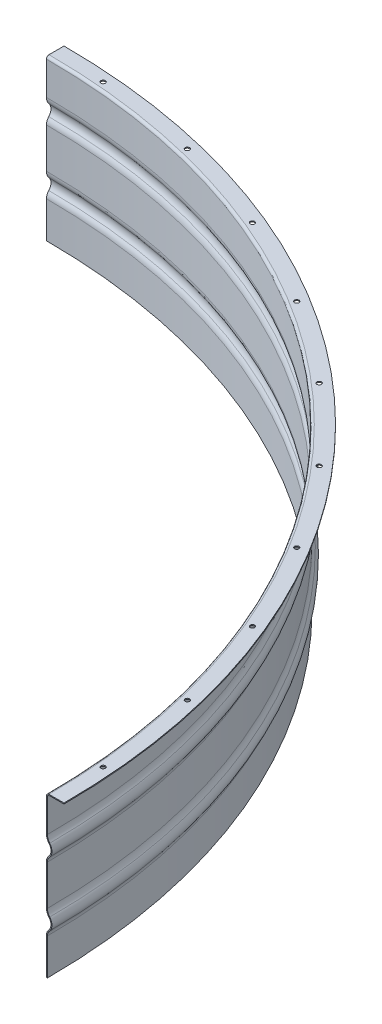
SolidWorks part; units mm, degrees
ref_plane "Front Plane" through (0, 0, 0) normal (0, 0, 1) x (1, 0, 0)
ref_plane "Top Plane" through (0, 0, 0) normal (0, 1, 0) x (1, 0, 0)
ref_plane "Right Plane" through (0, 0, 0) normal (1, 0, 0) x (0, 0, -1)
sketch "Sketch1" plane through (0, 0, 0) normal (1, 0, 0) x (0, 0, -1)
  line L0 (1713.6591, 1048.0054) -> (1666.6591, 1048.0054)
  line L1 (1658.6591, 1040.0054) -> (1658.6591, 936.4391)
  line L2 (1658.6591, 861.8519) -> (1658.6591, 736.4391)
  line L3 (1658.6591, 661.8519) -> (1658.6591, 548.0054)
  line L4 (1713.6591, 1045.0054) -> (1666.6591, 1045.0054)
  line L5 (1661.6591, 1040.0054) -> (1661.6591, 936.4391)
  line L6 (1661.6591, 861.8519) -> (1661.6591, 736.4391)
  line L7 (1661.6591, 661.8519) -> (1661.6591, 548.0054)
  line L8 (1661.6591, 548.0054) -> (1658.6591, 548.0054)
  line L9 (1713.6591, 1048.0054) -> (1713.6591, 1045.0054)
  line L10 (-336.3409, 1001.4955) -> (-336.3409, 321.842)
  arc A0 (1666.6591, 1048.0054) -> (1658.6591, 1040.0054) centre (1666.6591, 1040.0054) ccw
  arc A1 (1658.6591, 936.4391) -> (1666.68, 914.6889) centre (1692.1591, 936.4391) ccw
  arc A2 (1665.9861, 880.5416) -> (1666.68, 914.6889) centre (1647.1363, 898.0054) ccw
  arc A3 (1665.9861, 880.5416) -> (1658.6591, 861.8519) centre (1686.1591, 861.8519) ccw
  arc A4 (1658.6591, 736.4391) -> (1666.68, 714.6889) centre (1692.1591, 736.4391) ccw
  arc A5 (1665.9861, 680.5416) -> (1666.68, 714.6889) centre (1647.1363, 698.0054) ccw
  arc A6 (1665.9861, 680.5416) -> (1658.6591, 661.8519) centre (1686.1591, 661.8519) ccw
  arc A7 (1666.6591, 1045.0054) -> (1661.6591, 1040.0054) centre (1666.6591, 1040.0054) ccw
  arc A8 (1661.6591, 936.4391) -> (1668.9617, 916.6367) centre (1692.1591, 936.4391) ccw
  arc A9 (1668.1868, 878.5027) -> (1668.9617, 916.6367) centre (1647.1363, 898.0054) ccw
  arc A10 (1668.1868, 878.5027) -> (1661.6591, 861.8519) centre (1686.1591, 861.8519) ccw
  arc A11 (1661.6591, 736.4391) -> (1668.9617, 716.6367) centre (1692.1591, 736.4391) ccw
  arc A12 (1668.1868, 678.5027) -> (1668.9617, 716.6367) centre (1647.1363, 698.0054) ccw
  arc A13 (1668.1868, 678.5027) -> (1661.6591, 661.8519) centre (1686.1591, 661.8519) ccw
revolve "Revolve1" add sketch "Sketch1" angle 90 about L10
sketch "Sketch2" plane through (0, 1048.0054, 0) normal (0, 1, 0) x (1, 0, 0)
  circle A1 centre (158.4874, 1677.4321) radius 7
  dimension "D2" = 14
extrude "Cut-Extrude1" cut sketch "Sketch2" against normal through all both and the other way through all
pattern_circular "CirPattern1" count 10 every 9 about axis through (0, 0, 336.3409) along (0, 1, 0) of "Cut-Extrude1"
